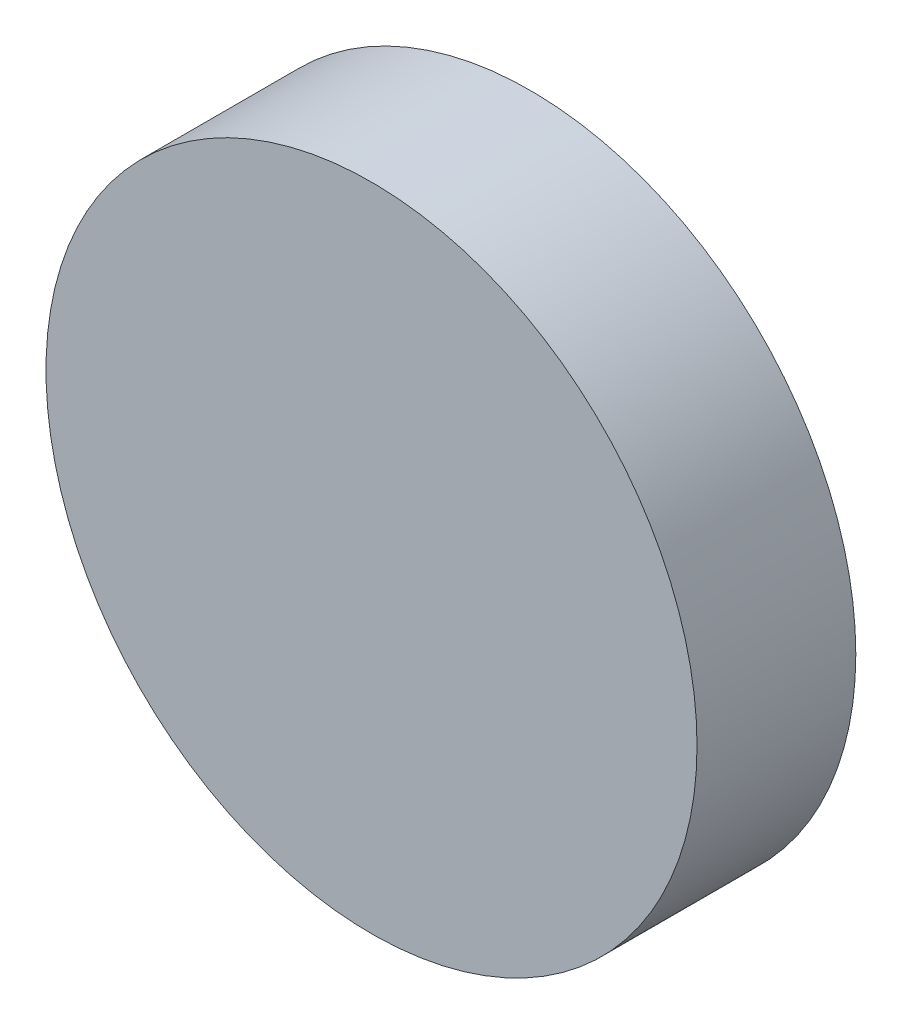
SolidWorks part; units mm, degrees
ref_plane "Front Plane" through (0, 0, 0) normal (0, 0, 1) x (1, 0, 0)
ref_plane "Top Plane" through (0, 0, 0) normal (0, 1, 0) x (1, 0, 0)
ref_plane "Right Plane" through (0, 0, 0) normal (1, 0, 0) x (0, 0, -1)
sketch "Sketch1" plane through (0, 0, 0) normal (0, 0, 1) x (1, 0, 0)
  circle A0 centre (0, 0) radius 61.5
  dimension "D1" = 123
extrude "Boss-Extrude1" add sketch "Sketch1" along normal mid plane 30
